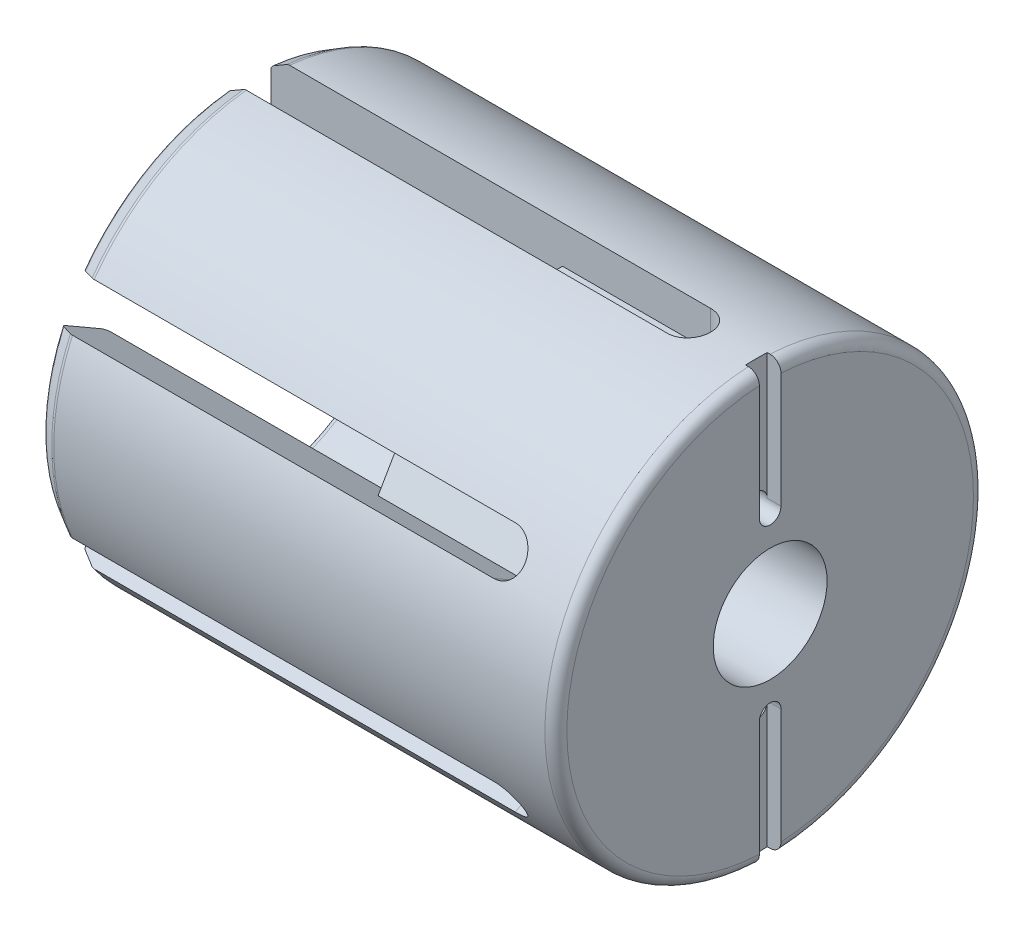
SolidWorks part; units mm, degrees
material "Invar 36"
ref_plane "Front Plane" through (0, 0, 0) normal (0, 0, 1) x (1, 0, 0)
ref_plane "Top Plane" through (0, 0, 0) normal (0, 1, 0) x (1, 0, 0)
ref_plane "Right Plane" through (0, 0, 0) normal (1, 0, 0) x (0, 0, -1)
sketch "Sketch1" plane through (0, 0, 0) normal (0, 0, 1) x (1, 0, 0)
  line L0 (-37.1799, 15.8623) -> (0, 15.8623)
  line L1 (0, 15.8623) -> (0, 0)
  line L2 (0, 0) -> (-16.9688, 0)
  line L3 (-16.9688, 0) -> (-16.9688, 11.43)
  line L4 (-16.9688, 11.43) -> (-38.1524, 11.43)
  line L5 (-38.5588, 11.8364) -> (-38.5588, 14.8944)
  line L6 (-38.3556, 15.2464) -> (-37.3831, 15.8079)
  line L7 (0, 0) -> (12.8646, 0) construction
  arc A0 (-38.5588, 14.8944) -> (-38.3556, 15.2464) centre (-38.1524, 14.8944) cw
  arc A1 (-38.1524, 11.43) -> (-38.5588, 11.8364) centre (-38.1524, 11.8364) cw
  arc A2 (-37.1799, 15.8623) -> (-37.3831, 15.8079) centre (-37.1799, 15.4559) ccw
  point P11 (-37.2888, 15.8623)
  point P13 (-16.9688, 11.43)
  point P17 (-38.5588, 11.43)
  dimension "D11" = 0.4064
  dimension "D12" = 0.4064
  dimension "D7" = 0.4064
  dimension "D1" = 31.7246
  dimension "D2" = 22.86
  dimension "D3" = 30
  dimension "D4" = 1.27
  dimension "D5" = 21.59
  dimension "D6" = 38.5588
revolve "Revolve1" add sketch "Sketch1" angle 360 about L7
hole_wizard "Tapped Hole for 5/16-18 Helicoil1" positions "Sketch2" profile "Sketch3" tap size "5/16-18" standard "Helicoil® Inch"
sketch "Sketch2" plane through (0, 0, 0) normal (1, 0, 0) x (0, 0, -1)
  point P0 (0, 0)
sketch "Sketch3" plane through (0, 0, 0) normal (0, 1, 0) x (0, 0, -1)
  line L0 (0, 0) -> (0, 31.3117)
  line L1 (0, 31.3117) -> (4.2164, 28.7782)
  line L2 (4.2164, 28.7782) -> (4.2164, 0)
  line L5 (4.2164, 0) -> (0, 0)
  line L10 (0, 31.3117) -> (-4.2164, 28.7782) construction
  line L11 (0, -6.35) -> (0, 107.95) construction
  dimension "Tap Drill Dia." = 8.4328
  dimension "Tap Drill Depth" = 28.7782
  dimension "Drill Angle" = 118
cosmetic thread "Hole Thread1" parameters "D1"=19.2532, "D2"=9.8654
sketch "Sketch4" plane through (-38.5588, 0, 0) normal (-1, 0, 0) x (0, 0, 1)
  line L0 (-1.6002, 15.7814) -> (-1.6002, 11.3174)
  line L1 (1.6002, 15.7814) -> (1.6002, 11.3174)
  circle A0 centre (0, 0) radius 11.43 construction
  circle A1 centre (0, 0) radius 15.8623 construction
  arc A2 (1.6002, 11.3174) -> (-1.6002, 11.3174) centre (0, 0) ccw
  arc A3 (1.6002, 15.7814) -> (-1.6002, 15.7814) centre (0, 0) ccw
  dimension "D1" = 1.6002
  dimension "D2" = 3.2004
extrude "Cut-Extrude1" cut sketch "Sketch4" against normal up to surface (21.59 mm away) up to face at (-16.9688, 0, -4.2164)
pattern_circular "CirPattern1" count 6 over 360 about axis through (0, 0, 0) along (1, 0, 0) of "Cut-Extrude1"
ref_plane "Plane1" through (0, 20, 0) normal (0, 1, 0) x (1, 0, 0)
sketch "Sketch5" plane through (0, 20, 0) normal (0, 1, 0) x (1, 0, 0)
  line L0 (-16.9688, 1.6002) -> (-6, 1.6002)
  line L1 (0, -15.8623) -> (0, 15.8623) construction
  line L2 (-16.9688, 1.6002) -> (-16.9688, -1.6002)
  line L3 (-16.9688, -1.6002) -> (-6, -1.6002)
  line L4 (-16.9688, 1.6002) -> (-37.1799, 1.6002) construction
  line L5 (-16.9688, -1.6002) -> (-37.1799, -1.6002) construction
  line L8 (-16.9688, 1.6002) -> (-16.9688, -1.6002) construction
  arc A0 (-6, -1.6002) -> (-6, 1.6002) centre (-6, 0) ccw
  dimension "D1" = 6
extrude "Cut-Extrude2" cut sketch "Sketch5" against normal blind 7
pattern_circular "CirPattern2" count 6 over 360 about axis through (0, 0, 0) along (1, 0, 0) of "Cut-Extrude2"
sketch "Sketch6" plane through (-16.9688, 0, 0) normal (-1, 0, 0) x (0, 0, 1)
  line L0 (0, 6.5) -> (0, 0) construction
  circle A0 centre (0, 6.5) radius 0.8001
  dimension "D1" = 1.6002
  dimension "D2" = 6.5
extrude "Cut-Extrude3" cut sketch "Sketch6" against normal through all
pattern_circular "CirPattern3" count 2 over 360 about axis through (0, 0, 0) along (1, 0, 0) of "Cut-Extrude3"
sketch "Sketch7" plane through (0, 0, 0) normal (1, 0, 0) x (0, 0, -1)
  line L0 (0, 0) -> (18.6799, 0) construction
  line L2 (-0.8001, 15.8421) -> (-0.8001, 6.5)
  line L4 (0.8001, 15.8421) -> (0.8001, 6.5)
  line L5 (0.8001, -15.8421) -> (0.8001, -6.5)
  line L6 (-0.8001, -15.8421) -> (-0.8001, -6.5)
  circle A0 centre (0, 6.5) radius 0.8001 construction
  arc A1 (-0.8001, 6.5) -> (0.8001, 6.5) centre (0, 6.5) ccw
  circle A2 centre (0, 0) radius 15.8623 construction
  arc A3 (0.8001, 15.8421) -> (-0.8001, 15.8421) centre (0, 0) ccw
  arc A4 (0.8001, -15.8421) -> (-0.8001, -15.8421) centre (0, 0) cw
  arc A5 (-0.8001, -6.5) -> (0.8001, -6.5) centre (0, -6.5) cw
extrude "Cut-Extrude4" cut sketch "Sketch7" against normal blind 1.016
fillet "Fillet1" radius 0.8128 2 edges at (0, 0, -15.8623) (0, 0, 15.8623)
